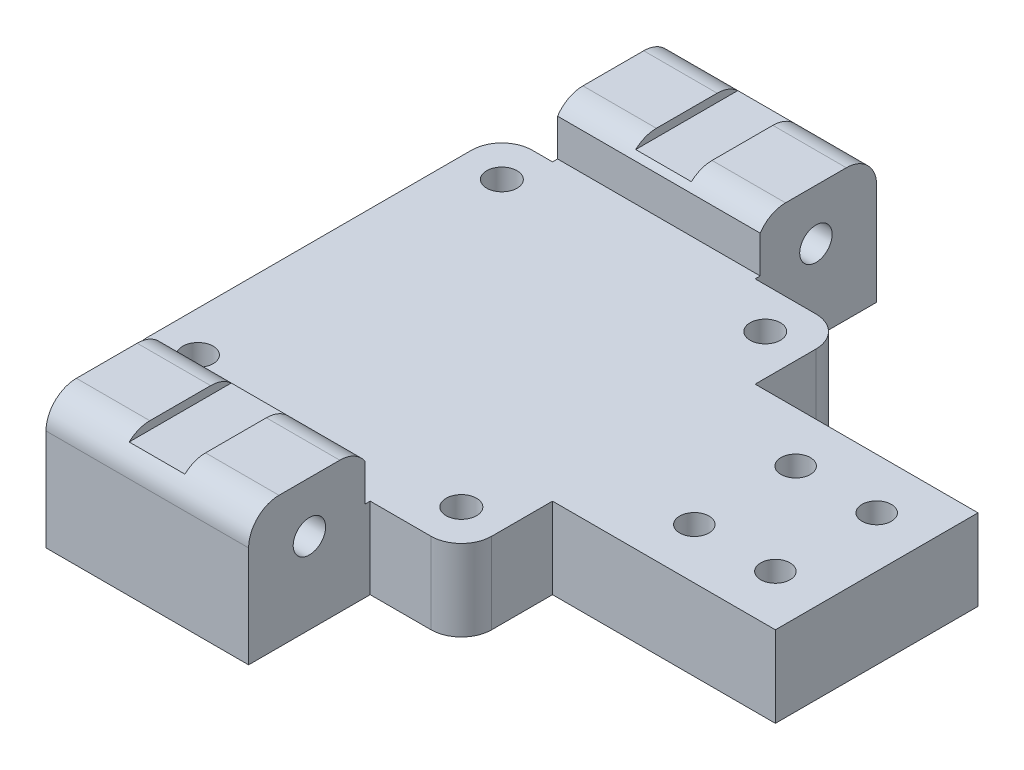
SolidWorks part; units mm, degrees
ref_plane "Front" through (0, 0, 0) normal (0, 0, 1) x (1, 0, 0)
ref_plane "Top" through (0, 0, 0) normal (0, 1, 0) x (1, 0, 0)
ref_plane "Right" through (0, 0, 0) normal (1, 0, 0) x (0, 0, -1)
sketch "Sketch1" plane through (0, 0, 0) normal (0, 1, 0) x (1, 0, 0)
  line L1 (0, 0) -> (300, 0)
  line L2 (0, 0) -> (0, -20)
  line L3 (0, -20) -> (300, -20)
  line L4 (300, 0) -> (300, -20)
  dimension "D1" = 20
  dimension "D2" = 300
extrude "Boss-Extrude1" add sketch "Sketch1" along normal blind 8
sketch "Sketch2" plane through (0, 0, 20) normal (0, 0, 1) x (1, 0, 0)
  line L0 (0, 8) -> (300, 8) construction
  line L1 (0, 0) -> (34, 0)
  line L2 (0, 0) -> (0, 8)
  line L3 (0, 8) -> (34, 8)
  line L4 (34, 0) -> (34, 8)
  line L5 (266, 8) -> (300, 8)
  line L6 (300, 0) -> (300, 8)
  line L7 (266, 0) -> (300, 0)
  line L8 (266, 0) -> (266, 8)
  dimension "D1" = 34
  dimension "D2" = 2
extrude "Boss-Extrude2" add sketch "Sketch2" along normal blind 9
sketch "Sketch3" plane through (0, 0, 0) normal (0, 0, -1) x (-1, 0, 0)
  line L0 (-300, 8) -> (0, 8) construction
  line L1 (0, 0) -> (-34, 0)
  line L2 (0, 0) -> (0, 8)
  line L3 (0, 8) -> (-34, 8)
  line L4 (-34, 0) -> (-34, 8)
  line L5 (-300, 0) -> (-300, 8)
  line L6 (-266, 8) -> (-300, 8)
  line L7 (-266, 0) -> (-266, 8)
  line L8 (-266, 0) -> (-300, 0)
  dimension "D1" = 34
  dimension "D2" = 2
extrude "Boss-Extrude3" add sketch "Sketch3" along normal blind 9
sketch "Sketch4" plane through (0, 8, 0) normal (0, 1, 0) x (1, 0, 0)
  line L0 (0, 9) -> (34, 9) construction
  line L1 (0, 9) -> (0, -29) construction
  circle A0 centre (4, 5) radius 1.5
  circle A1 centre (30, 5) radius 1.5
  circle A2 centre (30, -25) radius 1.5
  circle A3 centre (4, -25) radius 1.5
  circle A4 centre (296, -25) radius 1.5
  circle A5 centre (296, 5) radius 1.5
  circle A6 centre (270, -25) radius 1.5
  circle A7 centre (270, 5) radius 1.5
  dimension "D1" = 3
  dimension "D2" = 4
  dimension "D3" = 4
  dimension "D4" = 2
  dimension "D5" = 2
  dimension "D6" = 2
extrude "Cut-Extrude1" cut sketch "Sketch4" against normal through all
sketch "Sketch5" plane through (0, 0, 20) normal (0, 0, 1) x (1, 0, 0)
  line L0 (34, 8) -> (266, 8) construction
  line L1 (266, 0) -> (241, 0)
  line L2 (266, 0) -> (266, 8)
  line L3 (266, 8) -> (241, 8)
  line L4 (241, 0) -> (241, 8)
  dimension "D1" = 25
extrude "Boss-Extrude4" add sketch "Sketch5" along normal blind 17
sketch "Sketch6" plane through (0, 0, 0) normal (0, 0, -1) x (-1, 0, 0)
  line L0 (-266, 0) -> (-34, 0) construction
  line L1 (-266, 8) -> (-241, 8)
  line L2 (-266, 8) -> (-266, 0)
  line L3 (-266, 0) -> (-241, 0)
  line L4 (-241, 8) -> (-241, 0)
  dimension "D1" = 25
extrude "Boss-Extrude5" add sketch "Sketch6" along normal blind 17
sketch "Sketch7" plane through (0, 8, 0) normal (0, 1, 0) x (1, 0, 0)
  line L0 (266, -37) -> (241, -37) construction
  line L1 (259, -29) -> (249, -29)
  line L2 (259, -29) -> (259, 9)
  line L3 (259, 9) -> (249, 9)
  line L4 (249, -29) -> (249, 9)
  line L5 (241, -37) -> (241, -20) construction
  dimension "D1" = 10
  dimension "D2" = 38
  dimension "D3" = 8
  dimension "D4" = 8
extrude "Cut-Extrude2" cut sketch "Sketch7" against normal through all
sketch "Sketch8" plane through (0, 8, 0) normal (0, 1, 0) x (1, 0, 0)
  line L0 (259, -29) -> (259, 9) construction
  line L1 (259, -18) -> (266, -18)
  line L2 (259, -18) -> (259, -2)
  line L3 (259, -2) -> (266, -2)
  line L4 (266, -18) -> (266, -2)
  line L5 (266, -37) -> (241, -37) construction
  dimension "D1" = 7
  dimension "D2" = 16
  dimension "D3" = 19
extrude "Cut-Extrude3" cut sketch "Sketch8" against normal blind 4
sketch "Sketch9" plane through (259, 0, 0) normal (-1, 0, 0) x (0, 0, 1)
  line L0 (18, 4) -> (22, 8)
  line L1 (29, 8) -> (18, 8) construction
  line L2 (22, 8) -> (18, 8)
  line L3 (18, 8) -> (18, 4)
  line L4 (2, 4) -> (-2, 8)
  line L5 (2, 8) -> (-9, 8) construction
  line L6 (-2, 8) -> (2, 8)
  line L7 (2, 8) -> (2, 4)
  dimension "D1" = 4
  dimension "D2" = 4
extrude "Cut-Extrude4" cut sketch "Sketch9" against normal blind 7
sketch "Sketch10" plane through (259, 0, 0) normal (-1, 0, 0) x (0, 0, 1)
  line L0 (-9, 8) -> (-2, 0)
  line L1 (29, 0) -> (-9, 0) construction
  line L2 (-2, 0) -> (-9, 0)
  line L3 (-9, 0) -> (-9, 8)
  line L4 (29, 8) -> (22, 0)
  line L5 (22, 0) -> (29, 0)
  line L6 (29, 0) -> (29, 8)
  line L7 (-51.4523, 12.1971) -> (-51.8778, 12.5861)
  line M6 (-9, 8) -> (-9, 0)
  line M7 (-9, 0) -> (29, 0)
  line M8 (29, 0) -> (29, 8)
  dimension "D1" = 7
  dimension "D2" = 7
extrude "Boss-Extrude6" add sketch "Sketch10" along normal blind 10 contours L0 M6 M7 | L4 M8 M7
sketch "Sketch12" plane through (0, 0, 37) normal (0, 0, 1) x (1, 0, 0)
  line L0 (241, 0) -> (266, 0) construction
  line L1 (241, 8) -> (249, 8)
  line L2 (241, 8) -> (241, 0)
  line L3 (241, 0) -> (249, 0)
  line L4 (249, 8) -> (249, 0)
  dimension "D1" = 8
extrude "Boss-Extrude7" add sketch "Sketch12" along normal blind 17
sketch "Sketch13" plane through (0, 8, 0) normal (0, 1, 0) x (1, 0, 0)
  line L0 (249, -54) -> (241, -54) construction
  line L1 (249, -54) -> (249, -37) construction
  circle A0 centre (245, -50) radius 1.7
  circle A1 centre (245, -18) radius 1.7
  dimension "D1" = 3.4
  dimension "D2" = 4
  dimension "D3" = 4
  dimension "D4" = 2
extrude "Cut-Extrude6" cut sketch "Sketch13" against normal through all
sketch "Sketch14" plane through (0, 0, 29) normal (0, 0, 1) x (1, 0, 0)
  line L1 (295, 13) -> (275, 13)
  line L2 (295, 13) -> (295, 0)
  line L3 (295, 0) -> (275, 0)
  line L4 (275, 13) -> (275, 0)
  line L5 (266, 0) -> (300, 0) construction
  line L7 (266, 8) -> (266, 0) construction
  dimension "D1" = 20
  dimension "D2" = 9
  dimension "D3" = 13
extrude "Boss-Extrude8" add sketch "Sketch14" along normal blind 12
sketch "Sketch15" plane through (295, 0, 0) normal (1, 0, 0) x (0, 0, -1)
  line L0 (-41, 0) -> (-41, 13) construction
  line L1 (-41, 13) -> (-29, 13) construction
  circle A0 centre (-35, 8) radius 1.6
  dimension "D1" = 3.2
  dimension "D2" = 6
  dimension "D3" = 5
extrude "Cut-Extrude7" cut sketch "Sketch15" against normal blind 20
sketch "Sketch16" plane through (0, 0, -9) normal (0, 0, -1) x (-1, 0, 0)
  line L1 (-295, 13) -> (-275, 13)
  line L2 (-295, 13) -> (-295, 0)
  line L3 (-295, 0) -> (-275, 0)
  line L4 (-275, 13) -> (-275, 0)
  line L5 (-300, 0) -> (-266, 0) construction
  line L6 (-266, 0) -> (-266, 8) construction
  dimension "D1" = 20
  dimension "D2" = 9
  dimension "D3" = 13
extrude "Boss-Extrude9" add sketch "Sketch16" along normal blind 12
sketch "Sketch17" plane through (295, 0, 0) normal (1, 0, 0) x (0, 0, -1)
  line L1 (21, 13) -> (21, 0) construction
  line L2 (21, 13) -> (9, 13) construction
  circle A0 centre (15, 8) radius 1.6
  dimension "D1" = 3.2
  dimension "D2" = 5
  dimension "D3" = 6
extrude "Cut-Extrude8" cut sketch "Sketch17" against normal blind 20
sketch "Sketch18" plane through (0, 0, -9) normal (0, 0, -1) x (-1, 0, 0)
  line L1 (-25, 13) -> (-5, 13)
  line L2 (-25, 13) -> (-25, 0)
  line L3 (-25, 0) -> (-5, 0)
  line L4 (-5, 13) -> (-5, 0)
  line L5 (-34, 0) -> (0, 0) construction
  line L6 (-34, 8) -> (-34, 0) construction
  dimension "D1" = 20
  dimension "D2" = 9
  dimension "D3" = 13
extrude "Boss-Extrude10" add sketch "Sketch18" along normal blind 12
sketch "Sketch19" plane through (5, 0, 0) normal (-1, 0, 0) x (0, 0, 1)
  line L0 (-21, 0) -> (-21, 13) construction
  line L1 (-21, 13) -> (-9, 13) construction
  circle A0 centre (-15, 8) radius 1.6
  dimension "D1" = 3.2
  dimension "D2" = 6
  dimension "D3" = 5
extrude "Cut-Extrude9" cut sketch "Sketch19" against normal blind 20
sketch "Sketch20" plane through (0, 0, 29) normal (0, 0, 1) x (1, 0, 0)
  line L1 (5, 13) -> (25, 13)
  line L2 (5, 13) -> (5, 0)
  line L3 (5, 0) -> (25, 0)
  line L4 (25, 13) -> (25, 0)
  line L5 (0, 0) -> (34, 0) construction
  line L6 (34, 0) -> (34, 8) construction
  dimension "D1" = 20
  dimension "D2" = 9
  dimension "D3" = 13
extrude "Boss-Extrude11" add sketch "Sketch20" along normal blind 12
sketch "Sketch21" plane through (5, 0, 0) normal (-1, 0, 0) x (0, 0, 1)
  line L0 (41, 13) -> (41, 0) construction
  line L2 (41, 13) -> (29, 13) construction
  circle A0 centre (35, 8) radius 1.6
  dimension "D1" = 3.2
  dimension "D2" = 6
  dimension "D3" = 5
extrude "Cut-Extrude10" cut sketch "Sketch21" against normal blind 20
fillet "Fillet6" radius 3 8 edges at (15, 13, 41) (15, 13, 29) (15, 13, -9) (15, 13, -21) (285, 13, 41) (285, 13, 29) (285, 13, -9) (285, 13, -21)
sketch "Sketch22" plane through (300, 0, 0) normal (1, 0, 0) x (0, 0, -1)
  line L1 (-72.0035, 35.0177) -> (51.7473, 35.0177)
  line L2 (-72.0035, 35.0177) -> (-72.0035, -37.6215)
  line L3 (-72.0035, -37.6215) -> (51.7473, -37.6215)
  line L4 (51.7473, 35.0177) -> (51.7473, -37.6215)
extrude "Cut-Extrude11" cut sketch "Sketch22" against normal blind 244
sketch "Sketch23" plane through (0, 0, 0) normal (0, -1, 0) x (-1, 0, 0)
  line L0 (-34, -20) -> (-56, -20) construction
  line L1 (-56, -20) -> (-56, 0) construction
  line L2 (-56, 0) -> (-34, 0) construction
  circle A0 centre (-51, -5) radius 1.45
  circle A1 centre (-51, -15) radius 1.45
  circle A2 centre (-43, -5) radius 1.45
  circle A3 centre (-43, -15) radius 1.45
  dimension "D1" = 2.9
  dimension "D2" = 2.9
  dimension "D3" = 2.9
  dimension "D4" = 2.9
  dimension "D5" = 5
  dimension "D6" = 5
  dimension "D7" = 5
  dimension "D8" = 5
  dimension "D9" = 5
  dimension "D10" = 8
  dimension "D11" = 8
  dimension "D12" = 5
extrude "Cut-Extrude12" cut sketch "Sketch23" against normal through all
fillet "Fillet7" radius 3 4 edges at (0, 4, 29) (0, 4, -9) (34, 4, 29) (34, 4, -9)
sketch "Sketch24" plane through (0, 13, 0) normal (0, 1, 0) x (1, 0, 0)
  line L0 (5, 18) -> (5, 12) construction
  line L1 (12.25, 29.5448) -> (17.75, 29.5448)
  line L2 (12.25, 29.5448) -> (12.25, -48.6988)
  line L3 (12.25, -48.6988) -> (17.75, -48.6988)
  line L4 (17.75, 29.5448) -> (17.75, -48.6988)
  dimension "D1" = 5.5
  dimension "D2" = 7.25
extrude "Cut-Extrude13" cut sketch "Sketch24" against normal blind 0.8
sketch "Sketch25" plane through (0, 0, 29) normal (0, 0, -1) x (-1, 0, 0)
  line L1 (-25, 8) -> (-5, 8)
  line L2 (-25, 8) -> (-25, 13.7566)
  line L3 (-25, 13.7566) -> (-5, 13.7566)
  line L4 (-5, 8) -> (-5, 13.7566)
  dimension "D1" = 20
extrude "Cut-Extrude14" cut sketch "Sketch25" against normal blind 0.5
sketch "Sketch26" plane through (0, 0, -9) normal (0, 0, 1) x (1, 0, 0)
  line L1 (5, 8) -> (25, 8)
  line L2 (5, 8) -> (5, 29.4591)
  line L3 (5, 29.4591) -> (25, 29.4591)
  line L4 (25, 8) -> (25, 29.4591)
  dimension "D1" = 20
extrude "Cut-Extrude15" cut sketch "Sketch26" against normal blind 0.5
